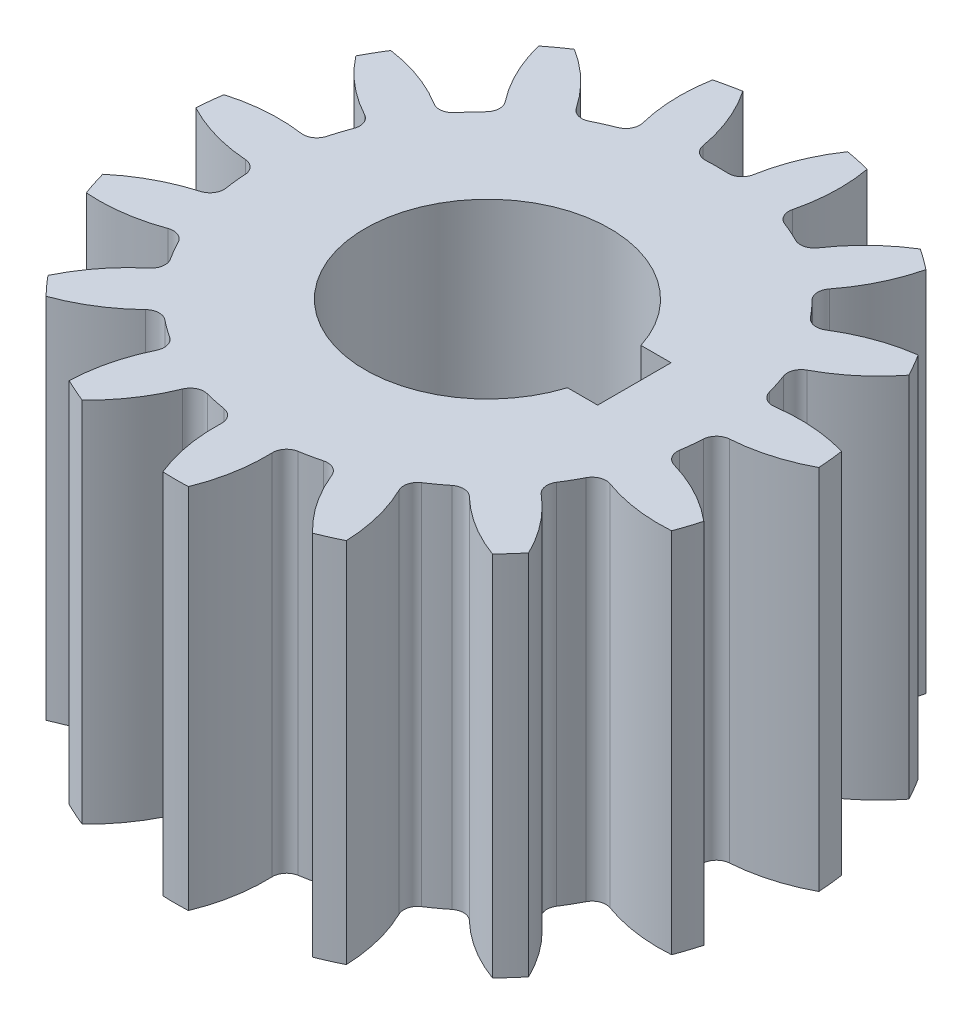
SolidWorks part; units mm, degrees
ref_plane "Front Plane" through (0, 0, 0) normal (0, 0, 1) x (1, 0, 0)
ref_plane "Top Plane" through (0, 0, 0) normal (0, 1, 0) x (1, 0, 0)
ref_plane "Right Plane" through (0, 0, 0) normal (1, 0, 0) x (0, 0, -1)
sketch "Sketch1" plane through (0, 0, 0) normal (0, 1, 0) x (1, 0, 0)
  circle A0 centre (0, 0) radius 5
  circle A1 centre (0, 0) radius 12.75
  dimension "D1" = 10
  dimension "D2" = 25.5
extrude "Boss-Extrude1" add sketch "Sketch1" along normal blind 15
sketch "Sketch2" plane through (0, 0, 0) normal (0, 1, 0) x (1, 0, 0)
  line L0 (0, 0) -> (0, 12.75) construction
  line L1 (0, 0) -> (-0.9571, 9.326) construction
  line L2 (0, 7.3224) -> (-5.528, 22.5103) construction
  arc A0 (0.9571, 9.326) -> (-0.9571, 9.326) centre (0, 0) ccw
  arc A1 (1.3995, 11.1626) -> (-1.3995, 11.1626) centre (0, 0) ccw construction
  arc A2 (2.1376, 12.5695) -> (-2.1376, 12.5695) centre (0, 0) ccw
  arc A3 (-2.1376, 12.5695) -> (-0.9571, 9.326) centre (-7.9845, 8.6048) cw
  arc A4 (2.1376, 12.5695) -> (0.9571, 9.326) centre (7.9845, 8.6048) ccw
  point P14 (-2.764, 14.9163)
  point P17 (-1.3462, 11.021)
  dimension "D1" = 25.5
  dimension "D2" = 22.5
  dimension "D3" = 3.375
  dimension "D4" = 20
  dimension "D5" = 2.8062
extrude "Cut-Extrude1" cut sketch "Sketch2" along normal blind 15 contours A2 A3 A0 A4
fillet "Fillet1" radius 0.57 2 edges at (0.9571, 7.5, -9.326) (-0.9571, 7.5, -9.326)
pattern_circular "CirPattern1" count 15 over 360 about axis through (0, 0, 0) along (0, 1, 0) of "Fillet1", "Cut-Extrude1"
sketch "Sketch3" plane through (0, 15, 0) normal (0, 1, 0) x (1, 0, 0)
  line L0 (0, -1.5) -> (6, -1.5)
  line L1 (0, 0) -> (6, 0) construction
  line L2 (0, -1.5) -> (0, 1.5)
  line L3 (0, 1.5) -> (6, 1.5)
  line L4 (6, -1.5) -> (6, 1.5)
  dimension "D1" = 1.5
  dimension "D2" = 6
extrude "Cut-Extrude2" cut sketch "Sketch3" against normal up to next
scale "Scale1" scale about centroid uniform scaling yes scale factor 10
equation "\"num_teeth\"= 15"
equation "\"outer_diameter\"= ( \"num_teeth\" + 2 ) * \"module\""
equation "\"module\"= 1.5"
equation "\"pitch_diameter\"= \"num_teeth\" * \"module\""
equation "\"arc_length\"= \"module\" * pi / 2 + \"backlash\""
equation "\"backlash\"= 0.3 * \"module\""
equation "\"Tooth_depth\"= IIF ( \"module\" <= 1.25 , \"module\" * 2.4 , \"module\" * 2.25 )"
equation "\"bore_diameter\"= 5"
equation "\"D2@Sketch1\"=\"outer_diameter\""
equation "\"D1@Sketch2\"=\"outer_diameter\""
equation "\"D2@Sketch2\"=\"pitch_diameter\""
equation "\"D3@Sketch2\"=\"Tooth_depth\""
equation "\"pitch_angle\"=20"
equation "\"D4@Sketch2\"=\"pitch_angle\""
equation "\"D5@Sketch2\"=\"arc_length\""
equation "\"fillet_radius\"= 0.38 * \"module\""
equation "\"D1@Fillet1\"=\"fillet_radius\""
equation "\"D1@CirPattern1\"=\"num_teeth\""
